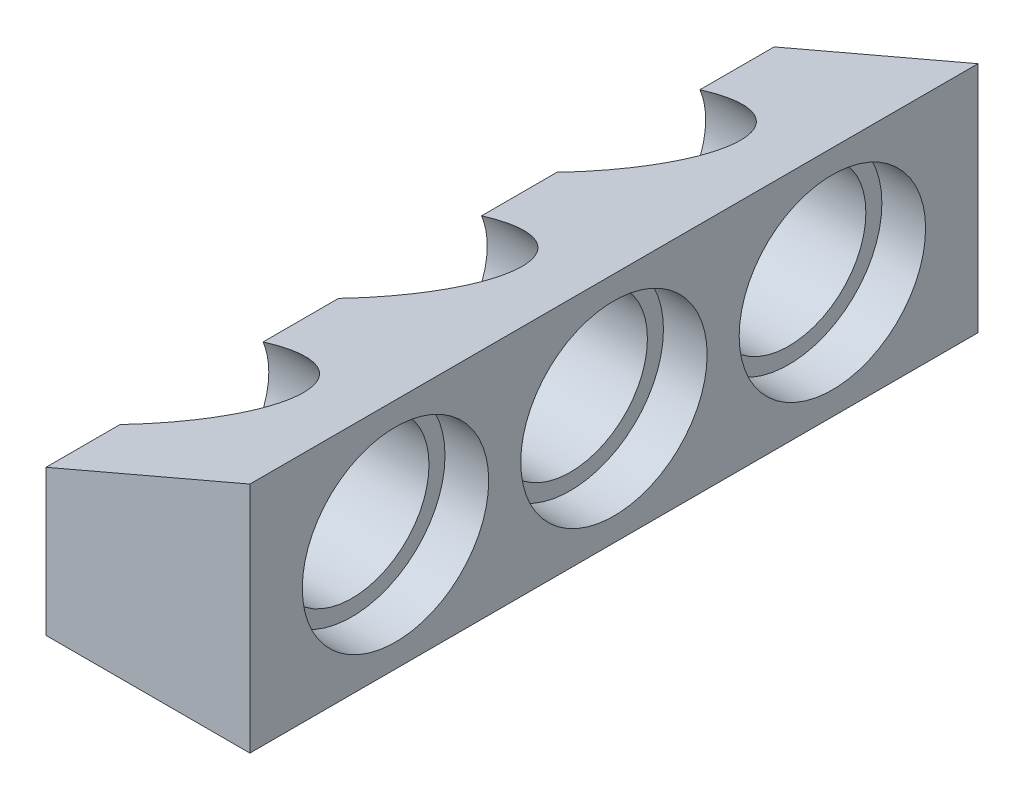
SolidWorks part; units mm, degrees
ref_plane "Plan de face" through (0, 0, 0) normal (0, 0, 1) x (1, 0, 0)
ref_plane "Plan de dessus" through (0, 0, 0) normal (0, 1, 0) x (1, 0, 0)
ref_plane "Plan de droite" through (0, 0, 0) normal (1, 0, 0) x (0, 0, -1)
sketch "Esquisse1" plane through (0, 0, 0) normal (0, 0, 1) x (1, 0, 0)
  line L0 (0, 0) -> (7, 0)
  line L1 (7, 0) -> (7, 8)
  line L2 (7, 8) -> (0, 5)
  line L3 (0, 5) -> (0, 0)
extrude "Boss.-Extru.1" add sketch "Esquisse1" along normal blind 25
sketch "Esquisse2" plane through (0, 0, 0) normal (-1, 0, 0) x (0, 0, 1)
  line L0 (0, 0) -> (0, 4) construction
  line L1 (0, 5) -> (0, 0) construction
  line L2 (0, 4) -> (5, 4) construction
  line L3 (5, 4) -> (12.5, 4) construction
  line L4 (12.5, 4) -> (20, 4) construction
  line L5 (20, 4) -> (25, 4) construction
  line L6 (25, 5) -> (25, 0) construction
  circle A0 centre (5, 4) radius 2.65
  circle A1 centre (12.5, 4) radius 2.65
  circle A2 centre (20, 4) radius 2.65
extrude "Enlèv. mat.-Extru.1" cut sketch "Esquisse2" against normal through all
sketch "Esquisse3" plane through (7, 0, 0) normal (1, 0, 0) x (0, 0, -1)
  circle A0 centre (-20, 4) radius 3.2
  circle A1 centre (-12.5, 4) radius 3.2
  circle A2 centre (-5, 4) radius 3.2
extrude "Enlèv. mat.-Extru.2" cut sketch "Esquisse3" against normal blind 1.5
